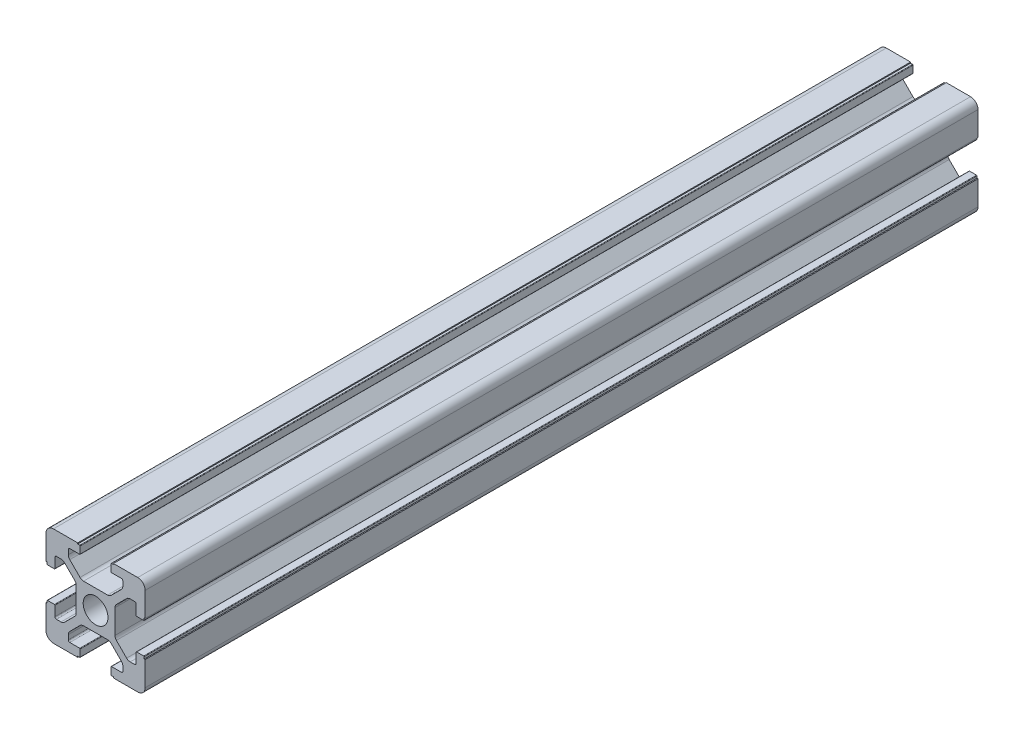
SolidWorks part; units mm, degrees
material "6063-T5"
ref_plane "前视基准面" through (0, 0, 0) normal (0, 0, 1) x (1, 0, 0)
ref_plane "上视基准面" through (0, 0, 0) normal (0, 1, 0) x (1, 0, 0)
ref_plane "右视基准面" through (0, 0, 0) normal (1, 0, 0) x (0, 0, -1)
sketch "草图1" plane through (0, 0, 0) normal (0, 0, 1) x (1, 0, 0)
  line L0 (-1.4389, 10) -> (24.3741, 10) construction
  line L1 (20, 13.6) -> (20, 20)
  line L2 (0, 0) -> (0, 6.4)
  line L3 (0, 20) -> (6.4, 20)
  line L4 (20, 0) -> (20, 6.4)
  line L5 (10, 21.5388) -> (10, -2.4017) construction
  line L6 (6.9, 18.3) -> (6.9, 19.7)
  line L7 (6.8, 18.2) -> (4.8, 18.2)
  line L8 (4.5, 17.9) -> (4.5, 16.9749)
  line L9 (4.7929, 16.2678) -> (6.8678, 14.1929)
  line L10 (7.5749, 13.9) -> (12.4251, 13.9)
  line L11 (6.8, 19.8) -> (6.4, 19.8)
  line L12 (6.4, 19.8) -> (6.4, 20)
  line L13 (0, 13.6) -> (0.2, 13.6)
  line L14 (0.2, 13.6) -> (0.2, 13.2)
  line L15 (0.3, 13.1) -> (1.7, 13.1)
  line L16 (1.8, 13.2) -> (1.8, 15.2)
  line L17 (2.1, 15.5) -> (3.0251, 15.5)
  line L18 (3.7322, 15.2071) -> (5.8071, 13.1322)
  line L19 (6.1, 12.4251) -> (6.1, 7.5749)
  line L20 (13.6, 19.8) -> (13.6, 20)
  line L21 (13.2, 19.8) -> (13.6, 19.8)
  line L22 (13.1, 18.3) -> (13.1, 19.7)
  line L23 (13.2, 18.2) -> (15.2, 18.2)
  line L24 (15.5, 17.9) -> (15.5, 16.9749)
  line L25 (15.2071, 16.2678) -> (13.1322, 14.1929)
  line L26 (0, 6.4) -> (0.2, 6.4)
  line L27 (0.2, 6.4) -> (0.2, 6.8)
  line L28 (0.3, 6.9) -> (1.7, 6.9)
  line L29 (1.8, 6.8) -> (1.8, 4.8)
  line L30 (2.1, 4.5) -> (3.0251, 4.5)
  line L31 (3.7322, 4.7929) -> (5.8071, 6.8678)
  line L32 (13.6, 20) -> (20, 20)
  line L33 (0, 13.6) -> (0, 20)
  line L34 (13.6, 0.2) -> (13.6, 0)
  line L35 (13.2, 0.2) -> (13.6, 0.2)
  line L36 (13.1, 1.7) -> (13.1, 0.3)
  line L37 (13.2, 1.8) -> (15.2, 1.8)
  line L38 (15.5, 2.1) -> (15.5, 3.0251)
  line L39 (15.2071, 3.7322) -> (13.1322, 5.8071)
  line L40 (4.5, 2.1) -> (4.5, 3.0251)
  line L41 (6.8, 1.8) -> (4.8, 1.8)
  line L42 (6.4, 0.2) -> (6.4, 0)
  line L43 (6.8, 0.2) -> (6.4, 0.2)
  line L44 (6.9, 1.7) -> (6.9, 0.3)
  line L45 (4.7929, 3.7322) -> (6.8678, 5.8071)
  line L46 (7.5749, 6.1) -> (12.4251, 6.1)
  line L47 (20, 6.4) -> (19.8, 6.4)
  line L48 (19.8, 6.4) -> (19.8, 6.8)
  line L49 (19.7, 6.9) -> (18.3, 6.9)
  line L50 (18.2, 6.8) -> (18.2, 4.8)
  line L51 (17.9, 4.5) -> (16.9749, 4.5)
  line L52 (16.2678, 4.7929) -> (14.1929, 6.8678)
  line L53 (13.9, 12.4251) -> (13.9, 7.5749)
  line L54 (16.2678, 15.2071) -> (14.1929, 13.1322)
  line L55 (17.9, 15.5) -> (16.9749, 15.5)
  line L56 (18.2, 13.2) -> (18.2, 15.2)
  line L57 (19.7, 13.1) -> (18.3, 13.1)
  line L58 (19.8, 13.6) -> (19.8, 13.2)
  line L59 (20, 13.6) -> (19.8, 13.6)
  line L60 (0, 0) -> (6.4, 0)
  line L61 (13.6, 0) -> (20, 0)
  arc A0 (6.1, 12.4251) -> (5.8071, 13.1322) centre (5.1, 12.4251) ccw
  arc A1 (7.5749, 13.9) -> (6.8678, 14.1929) centre (7.5749, 14.9) cw
  arc A2 (4.5, 16.9749) -> (4.7929, 16.2678) centre (5.5, 16.9749) ccw
  arc A3 (3.7322, 15.2071) -> (3.0251, 15.5) centre (3.0251, 14.5) ccw
  arc A4 (4.5, 17.9) -> (4.8, 18.2) centre (4.8, 17.9) cw
  arc A5 (1.8, 15.2) -> (2.1, 15.5) centre (2.1, 15.2) cw
  arc A6 (0.3, 13.1) -> (0.2, 13.2) centre (0.3, 13.2) cw
  arc A7 (6.9, 19.7) -> (6.8, 19.8) centre (6.8, 19.7) ccw
  arc A8 (1.7, 13.1) -> (1.8, 13.2) centre (1.7, 13.2) ccw
  arc A9 (6.9, 18.3) -> (6.8, 18.2) centre (6.8, 18.3) cw
  arc A10 (13.1, 19.7) -> (13.2, 19.8) centre (13.2, 19.7) cw
  arc A11 (13.1, 18.3) -> (13.2, 18.2) centre (13.2, 18.3) ccw
  arc A12 (15.5, 17.9) -> (15.2, 18.2) centre (15.2, 17.9) ccw
  arc A13 (15.5, 16.9749) -> (15.2071, 16.2678) centre (14.5, 16.9749) cw
  arc A14 (12.4251, 13.9) -> (13.1322, 14.1929) centre (12.4251, 14.9) ccw
  arc A15 (0.3, 6.9) -> (0.2, 6.8) centre (0.3, 6.8) ccw
  arc A16 (1.7, 6.9) -> (1.8, 6.8) centre (1.7, 6.8) cw
  arc A17 (1.8, 4.8) -> (2.1, 4.5) centre (2.1, 4.8) ccw
  arc A18 (3.7322, 4.7929) -> (3.0251, 4.5) centre (3.0251, 5.5) cw
  arc A19 (6.1, 7.5749) -> (5.8071, 6.8678) centre (5.1, 7.5749) cw
  arc A20 (13.1, 0.3) -> (13.2, 0.2) centre (13.2, 0.3) ccw
  arc A21 (13.1, 1.7) -> (13.2, 1.8) centre (13.2, 1.7) cw
  arc A22 (15.5, 2.1) -> (15.2, 1.8) centre (15.2, 2.1) cw
  arc A23 (15.5, 3.0251) -> (15.2071, 3.7322) centre (14.5, 3.0251) ccw
  arc A24 (12.4251, 6.1) -> (13.1322, 5.8071) centre (12.4251, 5.1) cw
  arc A25 (4.5, 2.1) -> (4.8, 1.8) centre (4.8, 2.1) ccw
  arc A26 (6.9, 0.3) -> (6.8, 0.2) centre (6.8, 0.3) cw
  arc A27 (6.9, 1.7) -> (6.8, 1.8) centre (6.8, 1.7) ccw
  arc A28 (4.5, 3.0251) -> (4.7929, 3.7322) centre (5.5, 3.0251) cw
  arc A29 (7.5749, 6.1) -> (6.8678, 5.8071) centre (7.5749, 5.1) ccw
  arc A30 (19.7, 6.9) -> (19.8, 6.8) centre (19.7, 6.8) cw
  arc A31 (18.3, 6.9) -> (18.2, 6.8) centre (18.3, 6.8) ccw
  arc A32 (18.2, 4.8) -> (17.9, 4.5) centre (17.9, 4.8) cw
  arc A33 (16.2678, 4.7929) -> (16.9749, 4.5) centre (16.9749, 5.5) ccw
  arc A34 (13.9, 7.5749) -> (14.1929, 6.8678) centre (14.9, 7.5749) ccw
  arc A35 (13.9, 12.4251) -> (14.1929, 13.1322) centre (14.9, 12.4251) cw
  arc A36 (16.2678, 15.2071) -> (16.9749, 15.5) centre (16.9749, 14.5) cw
  arc A37 (18.2, 15.2) -> (17.9, 15.5) centre (17.9, 15.2) ccw
  arc A38 (18.3, 13.1) -> (18.2, 13.2) centre (18.3, 13.2) cw
  arc A39 (19.7, 13.1) -> (19.8, 13.2) centre (19.7, 13.2) ccw
  circle A40 centre (10, 10) radius 2.5
  point P39 (0.2, 13.1)
  point P42 (6.9, 19.8)
  point P45 (1.8, 13.1)
  point P48 (6.9, 18.2)
  point P66 (10, 13.9)
  point P83 (6.1, 10)
  dimension "D19" = 1
  dimension "D20" = 1
  dimension "D21" = 0.3
  dimension "D22" = 0.1
  dimension "D23" = 5
  dimension "D1" = 20
  dimension "D2" = 20
  dimension "D3" = 10
  dimension "D4" = 10
  dimension "D5" = 1.8
  dimension "D6" = 0.5
  dimension "D7" = 1.6
  dimension "D8" = 3.1
  dimension "D9" = 6.1
  dimension "D10" = 5.5
  dimension "D11" = 3.1
  dimension "D12" = 6.1
  dimension "D13" = 5.5
  dimension "D14" = 1.8
  dimension "D15" = 0.5
  dimension "D16" = 1.5
  dimension "D17" = 45
  dimension "D18" = 1.6
extrude "凸台-拉伸1" add sketch "草图1" along normal blind 168
fillet "圆角1" radius 1.5 4 edges at (20, 0, 84) (0, 0, 84) (0, 20, 84) (20, 20, 84)
